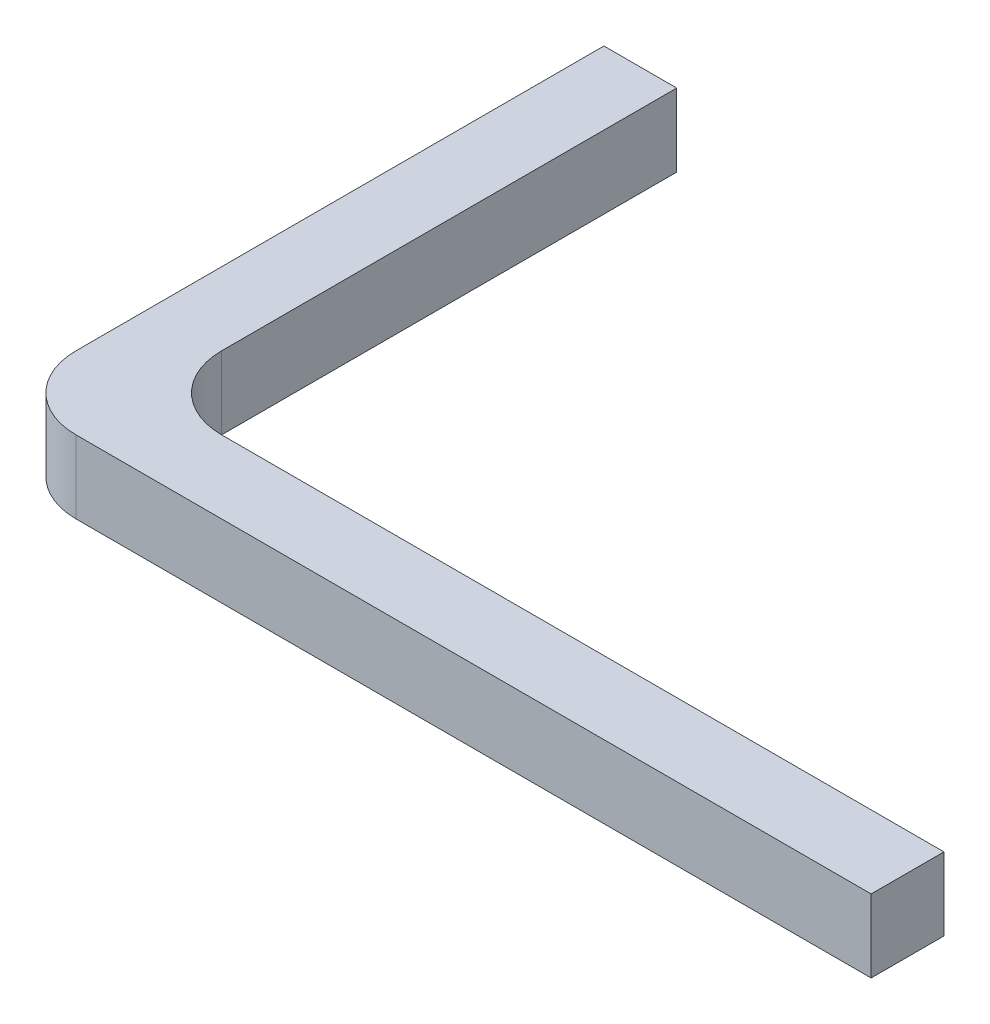
SolidWorks part; units mm, degrees
material "PTFE (general)"
ref_plane "Front Plane" through (0, 0, 0) normal (0, 0, 1) x (1, 0, 0)
ref_plane "Top Plane" through (0, 0, 0) normal (0, 1, 0) x (1, 0, 0)
ref_plane "Right Plane" through (0, 0, 0) normal (1, 0, 0) x (0, 0, -1)
sketch "Sketch1" plane through (0, 0, 0) normal (0, 1, 0) x (1, 0, 0)
  line L0 (-218.4, 10) -> (0, 10)
  line L1 (0, 10) -> (0, -10)
  line L2 (0, -10) -> (-238.4, -10)
  line L4 (-238.4, -10) -> (-238.4, 155)
  line L5 (-238.4, 155) -> (-218.4, 155)
  line L6 (-218.4, 155) -> (-218.4, 10)
  point P5 (0, 0)
  dimension "D1" = 238.4
  dimension "D2" = 20
  dimension "D3" = 165
  dimension "D4" = 20
extrude "Boss-Extrude1" add sketch "Sketch1" along normal blind 20
fillet "Fillet1" radius 20 2 edges at (-238.4, 10, 10) (-218.4, 10, -10)
